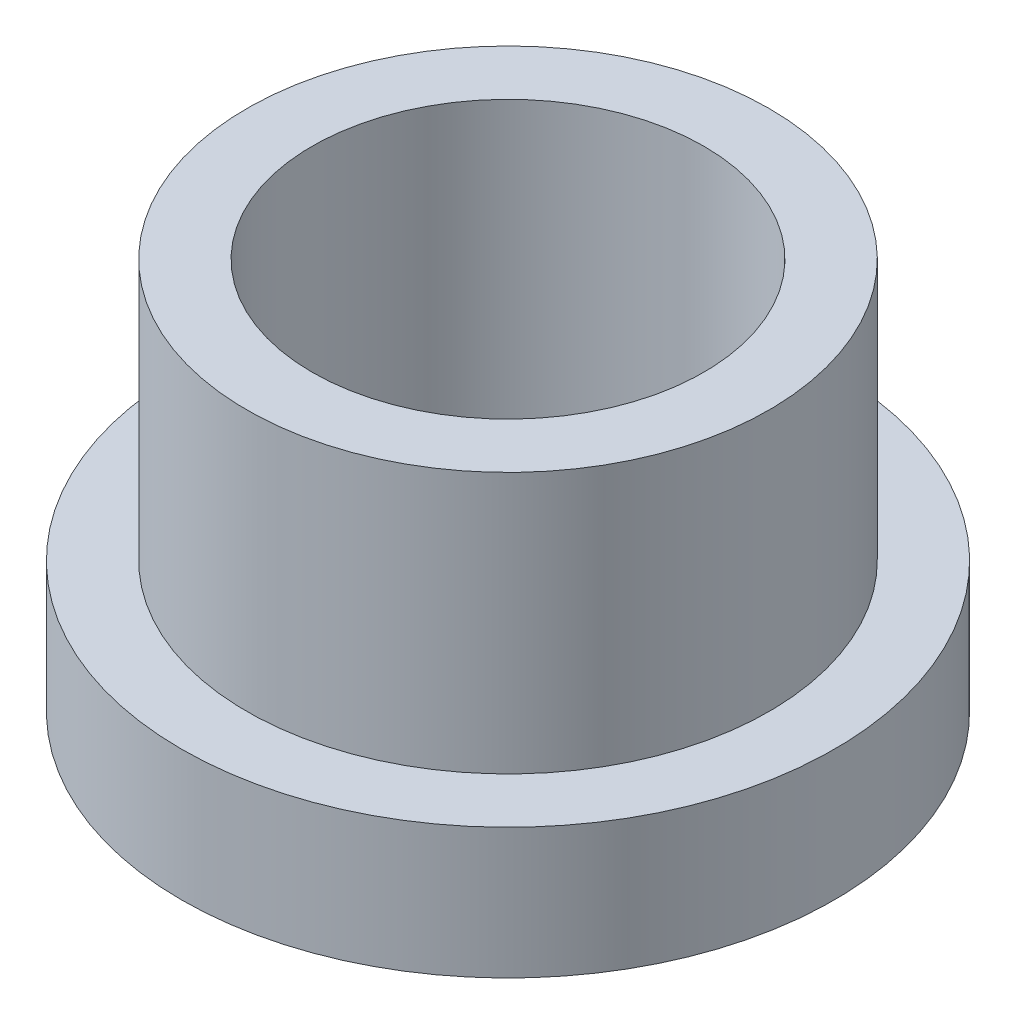
SolidWorks part; units mm, degrees
ref_plane "Front" through (0, 0, 0) normal (0, 0, 1) x (1, 0, 0)
ref_plane "Top" through (0, 0, 0) normal (0, 1, 0) x (1, 0, 0)
ref_plane "Right" through (0, 0, 0) normal (1, 0, 0) x (0, 0, -1)
sketch "Sketch1" plane through (0, 0, 0) normal (0, 1, 0) x (1, 0, 0)
  circle A0 centre (0, 0) radius 4.7625
  circle A1 centre (0, 0) radius 6.35
  circle A2 centre (0, 0) radius 7.9375
  dimension "ID" = 9.525
  dimension "OD" = 12.7
  dimension "FlangeOD" = 15.875
sketch "Sketch2" plane through (0, 0, 0) normal (0, 1, 0) x (1, 0, 0)
  circle A0 centre (0, 0) radius 4.7625 construction
  circle A1 centre (0, 0) radius 6.35 construction
  circle A2 centre (0, 0) radius 4.7625
  circle A3 centre (0, 0) radius 6.35
extrude "Boss-Extrude1" add sketch "Sketch2" along normal blind 9.525
sketch "Sketch3" plane through (0, 0, 0) normal (0, 1, 0) x (1, 0, 0)
  circle A0 centre (0, 0) radius 7.9375 construction
  circle A1 centre (0, 0) radius 6.35 construction
  circle A2 centre (0, 0) radius 7.9375
  circle A3 centre (0, 0) radius 6.35
extrude "Boss-Extrude2" add sketch "Sketch3" along normal blind 3.175
